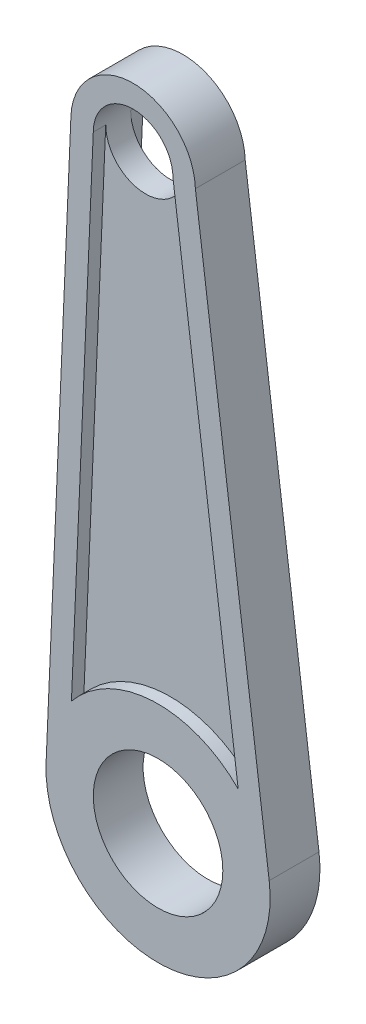
SolidWorks part; units mm, degrees
ref_plane "Front Plane" through (0, 0, 0) normal (0, 0, 1) x (1, 0, 0)
ref_plane "Top Plane" through (0, 0, 0) normal (0, 1, 0) x (1, 0, 0)
ref_plane "Right Plane" through (0, 0, 0) normal (1, 0, 0) x (0, 0, -1)
sketch "Sketch1" plane through (0, 0, 0) normal (0, 0, 1) x (1, 0, 0)
  line L0 (-12.4882, 52.3163) -> (-17.4768, -62.6534)
  line L1 (12.4936, 52.1753) -> (27.3107, -60.7003)
  line L2 (-8, 51.7744) -> (-12.3878, -49.3514)
  line L3 (8, 51.7744) -> (21.0832, -47.8918)
  circle A0 centre (0, 51.7744) radius 8
  arc A1 (-17.4768, -62.6534) -> (27.3107, -60.7003) centre (5.0021, -63.6287) ccw
  arc A4 (12.4936, 52.1753) -> (-12.4882, 52.3163) centre (0, 51.7744) ccw
  circle A5 centre (5.0021, -63.6287) radius 13
  arc A6 (21.0832, -47.8918) -> (-12.3878, -49.3514) centre (5.0021, -63.6287) ccw
  dimension "D2" = 16
  dimension "D3" = 45
  dimension "D4" = 26
extrude "Boss-Extrude1" add sketch "Sketch1" along normal blind 10 contours L1 A4 L0 A1 A5 L3 A6 L2 A0
ref_plane "Plane1" through (0, 0, 5) normal (0, 0, 1) x (1, 0, 0)
sketch "Sketch2" plane through (0, 0, 5) normal (0, 0, 1) x (1, 0, 0)
  line L0 (-8, 51.7744) -> (-12.3878, -49.3514) construction
  line L1 (8, 51.7744) -> (21.0832, -47.8918) construction
  line L2 (-12.4882, 52.3163) -> (-17.4768, -62.6534)
  line L3 (27.3107, -60.7003) -> (12.4936, 52.1753)
  line L4 (-12.4882, 52.3163) -> (-17.4768, -62.6534)
  line L5 (27.3107, -60.7003) -> (12.4936, 52.1753)
  line L6 (-8, 51.7744) -> (-12.3878, -49.3514)
  line L7 (8, 51.7744) -> (21.0832, -47.8918)
  arc A0 (21.0832, -47.8918) -> (-12.3878, -49.3514) centre (5.0021, -63.6287) ccw construction
  circle A1 centre (5.0021, -63.6287) radius 13
  circle A2 centre (5.0021, -63.6287) radius 13
  circle A3 centre (0, 51.7744) radius 8
  circle A4 centre (0, 51.7744) radius 8
  arc A5 (21.0832, -47.8918) -> (-12.3878, -49.3514) centre (5.0021, -63.6287) ccw
  arc A6 (-17.4768, -62.6534) -> (27.3107, -60.7003) centre (5.0021, -63.6287) ccw
  arc A7 (12.4936, 52.1753) -> (-12.4882, 52.3163) centre (0, 51.7744) ccw
  arc A8 (-17.4768, -62.6534) -> (27.3107, -60.7003) centre (5.0021, -63.6287) ccw
  arc A9 (12.4936, 52.1753) -> (-12.4882, 52.3163) centre (0, 51.7744) ccw
  dimension "D1" = 0
  dimension "D2" = 0
  dimension "D3" = 0
extrude "Boss-Extrude2" add sketch "Sketch2" along normal mid plane 5 contours A5 L7 A4 L6
